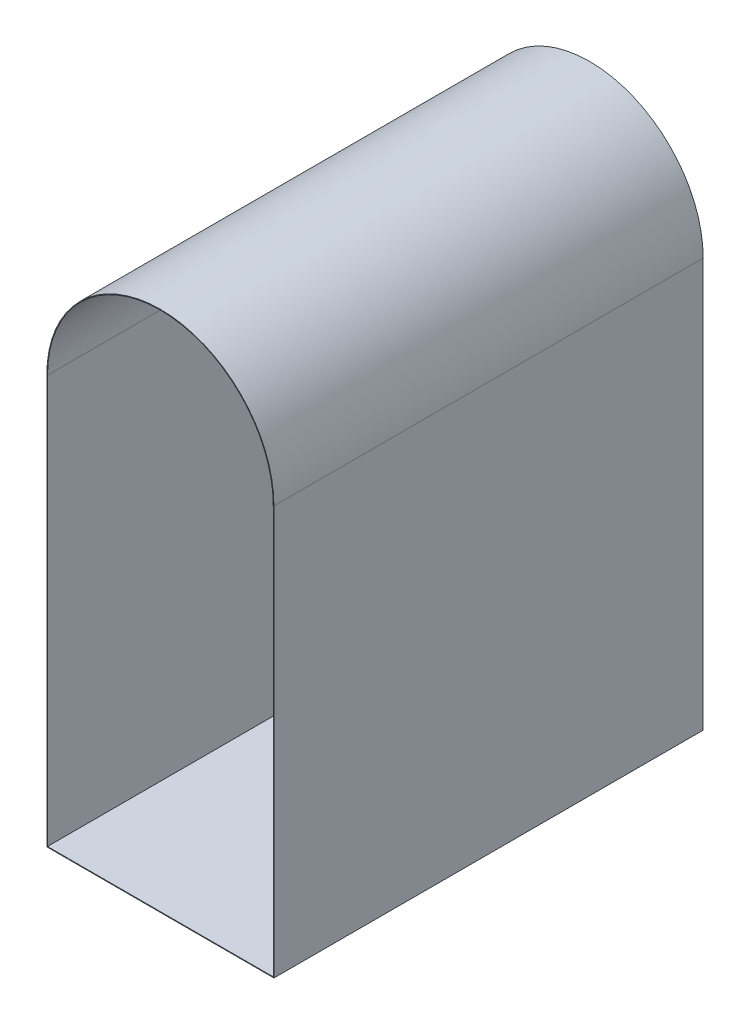
SolidWorks part; units mm, degrees
ref_plane "Front Plane" through (0, 0, 0) normal (0, 0, 1) x (1, 0, 0)
ref_plane "Top Plane" through (0, 0, 0) normal (0, 1, 0) x (1, 0, 0)
ref_plane "Right Plane" through (0, 0, 0) normal (1, 0, 0) x (0, 0, -1)
sketch "Sketch1" plane through (0, 0, 0) normal (0, 0, 1) x (1, 0, 0)
  line L0 (-50, -31.5253) -> (50, -31.5253)
  line L6 (50, -31.5253) -> (50, 148.4747)
  line L9 (-50, -31.5253) -> (-50, 148.4747)
  line L10 (0, 0) -> (0, -81.1266) construction
  arc A4 (-50, 148.4747) -> (50, 148.4747) centre (0, 148.4747) cw
  point P0 (0, 0)
  dimension "D1" = 50
  dimension "D2" = 180
  dimension "D3" = 50
extrude "Boss-Extrude1" add sketch "Sketch1" along normal blind 189
shell "Shell2" thickness 0.3
